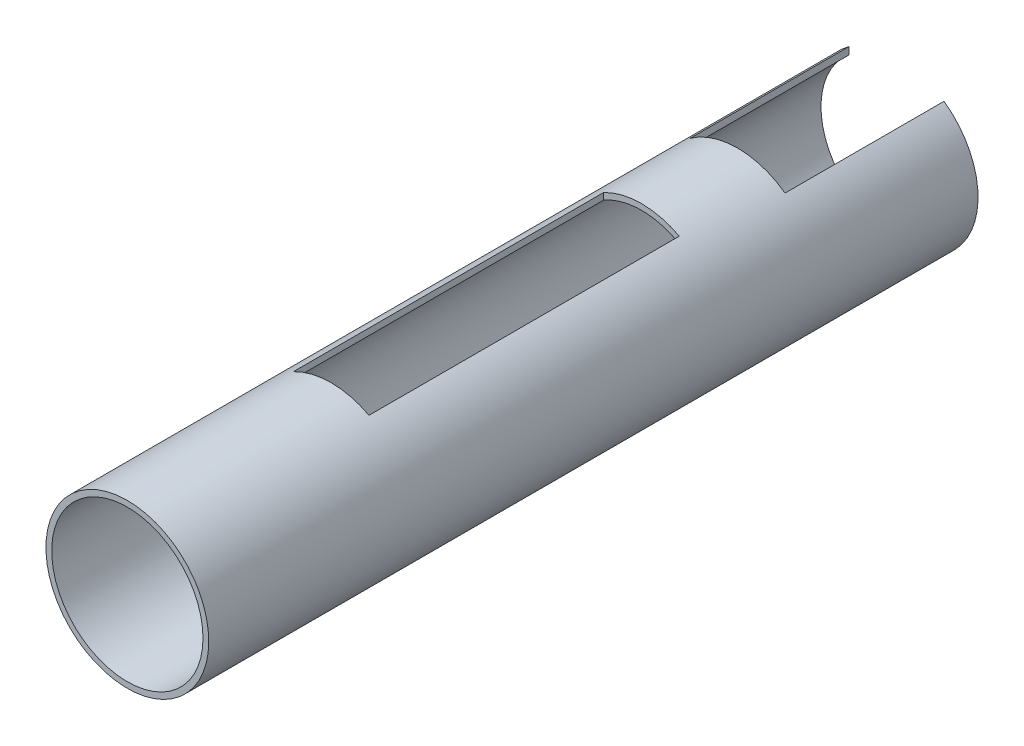
SolidWorks part; units mm, degrees
ref_plane "Front Plane" through (0, 0, 0) normal (0, 0, 1) x (1, 0, 0)
ref_plane "Top Plane" through (0, 0, 0) normal (0, 1, 0) x (1, 0, 0)
ref_plane "Right Plane" through (0, 0, 0) normal (1, 0, 0) x (0, 0, -1)
sketch "Sketch1" plane through (0, 0, 0) normal (0, 0, 1) x (1, 0, 0)
  circle A0 centre (0, 0) radius 31.75
  circle A1 centre (0, 0) radius 29.5
  dimension "D1" = 63.5
  dimension "D2" = 59
extrude "Boss-Extrude1" add sketch "Sketch1" along normal blind 300
sketch "Sketch2" plane through (0, 0, 0) normal (0, 1, 0) x (1, 0, 0)
  line L0 (31.75, 0) -> (-31.75, 0) construction
  line L1 (-18.5, 0) -> (18.5, 0)
  line L2 (-18.5, 0) -> (-18.5, -62)
  line L3 (-18.5, -62) -> (18.5, -62)
  line L4 (18.5, 0) -> (18.5, -62)
  point P6 (0, -62)
  dimension "D1" = 37
  dimension "D2" = 62
extrude "Cut-Extrude1" cut sketch "Sketch2" along normal up to surface (25.8033 mm away)
sketch "Sketch4" plane through (0, 0, 0) normal (0, 1, 0) x (1, 0, 0)
  line L0 (18.5, -62) -> (-18.5, -62) construction
  line L1 (-14.75, -99.5) -> (14.75, -99.5)
  line L2 (-14.75, -99.5) -> (-14.75, -220.5)
  line L3 (-14.75, -220.5) -> (14.75, -220.5)
  line L4 (14.75, -99.5) -> (14.75, -220.5)
  point P4 (0, -220.5)
  dimension "D1" = 29.5
  dimension "D2" = 121
  dimension "D3" = 37.5
extrude "Cut-Extrude2" cut sketch "Sketch4" against normal through all both and the other way through all
